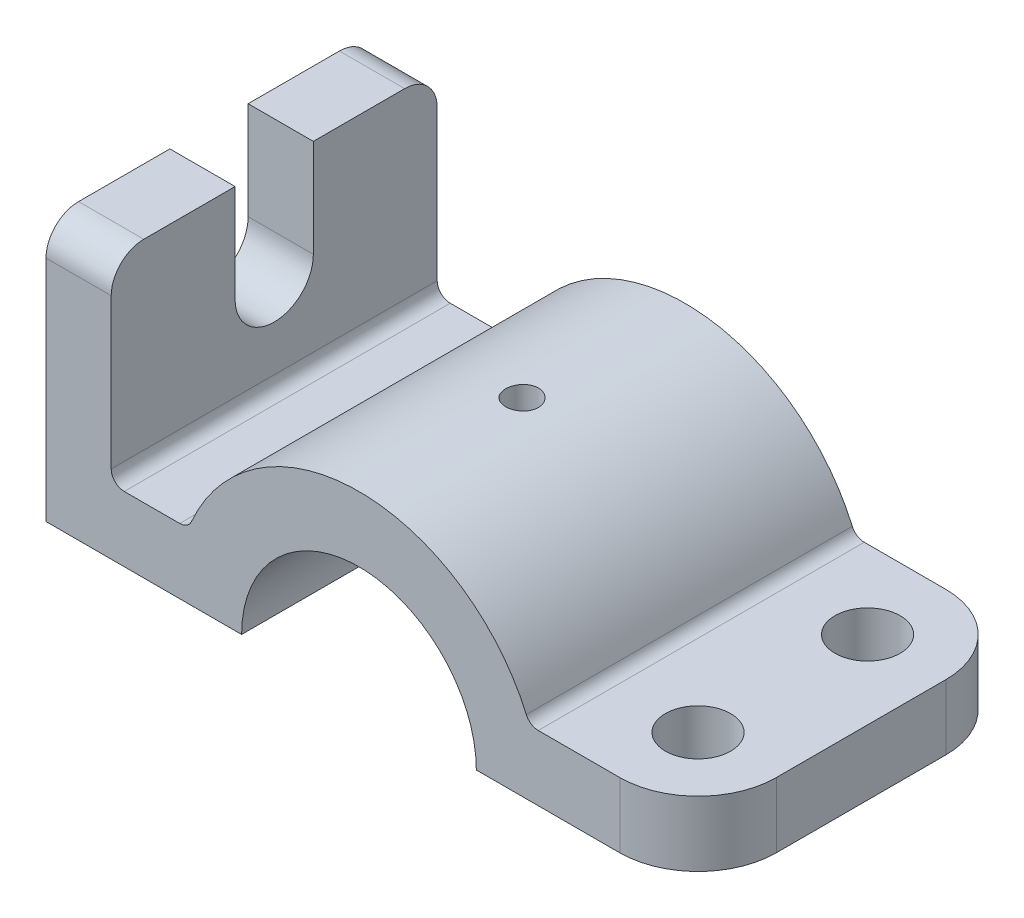
SolidWorks part; units mm, degrees
ref_plane "Front Plane" through (0, 0, 0) normal (0, 0, 1) x (1, 0, 0)
ref_plane "Top Plane" through (0, 0, 0) normal (0, 1, 0) x (1, 0, 0)
ref_plane "Right Plane" through (0, 0, 0) normal (1, 0, 0) x (0, 0, -1)
sketch "Sketch1" plane through (0, 0, 0) normal (0, 0, 1) x (1, 0, 0)
  line L0 (0, 46179.5999) -> (0, -18059.8784) construction
  line L1 (-65451.1081, 0) -> (70911.9676, 0) construction
  line L2 (18000, 0) -> (52000, 0)
  line L3 (52000, 0) -> (52000, 10000)
  line L4 (52000, 10000) -> (26153.3937, 10000)
  line L5 (-18000, 0) -> (-48000, 0)
  line L6 (-48000, 0) -> (-48000, 40000)
  line L7 (-48000, 40000) -> (-38000, 40000)
  line L8 (-38000, 40000) -> (-38000, 10000)
  line L9 (-38000, 10000) -> (-26153.3937, 10000)
  arc A0 (18000, 0) -> (-18000, 0) centre (0, 0) ccw
  arc A1 (26153.3937, 10000) -> (-26153.3937, 10000) centre (0, 0) ccw
  point P8 (0, 46179.5999)
  point P17 (-65451.1081, 0)
  point P18 (0, -18059.8784)
  point P19 (70911.9676, 0)
  dimension "D1" = 18000
  dimension "D2" = 28000
  dimension "D3" = 100000
  dimension "D4" = 48000
  dimension "D5" = 10000
  dimension "D6" = 10000
  dimension "D7" = 40000
  dimension "D8" = 10000
extrude "Boss-Extrude1" add sketch "Sketch1" against normal blind 50000
sketch "Sketch2" plane through (-48000, 0, 0) normal (-1, 0, 0) x (0, 0, 1)
  line L6 (-50000, 35000) -> (-50000, 40000)
  line L7 (-50000, 40000) -> (-45000, 40000)
  line L14 (0, 35000) -> (0, 40000)
  line L15 (0, 40000) -> (-5000, 40000)
  arc A1 (0, 35000) -> (-5000, 40000) centre (-5000, 35000) ccw
  arc A2 (-45000, 40000) -> (-50000, 35000) centre (-45000, 35000) ccw
  point P22 (0, 40000)
  point P26 (-50000, 40000)
  dimension "D5" = 5000
  dimension "D6" = 5000
extrude "Cut-Extrude1" cut sketch "Sketch2" against normal blind 10000
sketch "Sketch3" plane through (-48000, 0, 0) normal (-1, 0, 0) x (0, 0, 1)
  line L0 (-25000, 40000) -> (-25000, -6102.5717) construction
  line L1 (-45000, 40000) -> (-5000, 40000) construction
  line L2 (-57597.0553, 25000) -> (10718.9812, 25000) construction
  line L3 (-31000, 40000) -> (-19000, 40000)
  line L4 (-19000, 40000) -> (-19000, 25000)
  line L5 (-31000, 40000) -> (-31000, 25000)
  arc A0 (-19000, 25000) -> (-31000, 25000) centre (-25000, 25000) cw
  dimension "D1" = 25000
  dimension "D2" = 6000
  dimension "D3" = 12000
extrude "Cut-Extrude2" cut sketch "Sketch3" against normal blind 10000
fillet "Fillet1" radius 2000 2 edges at (-38000, 10000, -25000) (-26153.3937, 10000, -25000)
sketch "Sketch4" plane through (0, 10000, 0) normal (0, 1, 0) x (1, 0, 0)
  line L0 (52000, 38000) -> (52000, 50000)
  line L1 (52000, 12000) -> (52000, 0)
  line L3 (40000, 50000) -> (52000, 50000)
  line L4 (52000, 0) -> (40000, 0)
  arc A0 (52000, 12000) -> (40000, 0) centre (40000, 12000) cw
  arc A1 (52000, 38000) -> (40000, 50000) centre (40000, 38000) ccw
  point P10 (52000, 0)
  point P13 (52000, 50000)
  dimension "D1" = 12000
extrude "Cut-Extrude3" cut sketch "Sketch4" against normal blind 10000
fillet "Fillet2" radius 2000 1 edges at (26153.3937, 10000, -25000)
sketch "Sketch5" plane through (0, 10000, 0) normal (0, 1, 0) x (1, 0, 0)
  line L0 (33279.8644, 38000) -> (61860.8925, 38000) construction
  line L1 (33279.8644, 12000) -> (65367.7672, 12000) construction
  line L2 (40000, 0) -> (27495.4542, 0) construction
  line L3 (40000, 50000) -> (27495.4542, 50000) construction
  line L5 (40000, 50000) -> (40000, -9479.9203) construction
  circle A0 centre (40000, 12000) radius 5000
  circle A1 centre (40000, 38000) radius 5000
  dimension "D3" = 10000
  dimension "D4" = 10000
  dimension "D1" = 12000
  dimension "D2" = 12000
extrude "Cut-Extrude4" cut sketch "Sketch5" against normal blind 10000
sketch "Sketch6" plane through (0, 0, 0) normal (0, 1, 0) x (1, 0, 0)
  line L0 (-25662.4239, 25000) -> (59676.5239, 25000) construction
  line L1 (-25662.4239, 50000) -> (-25662.4239, 0) construction
  line L2 (-25662.4239, 0) -> (25662.4239, 0) construction
  circle A0 centre (0, 25000) radius 2500
  dimension "D2" = 5000
  dimension "D1" = 25000
extrude "Cut-Extrude5" cut sketch "Sketch6" along normal blind 100000
